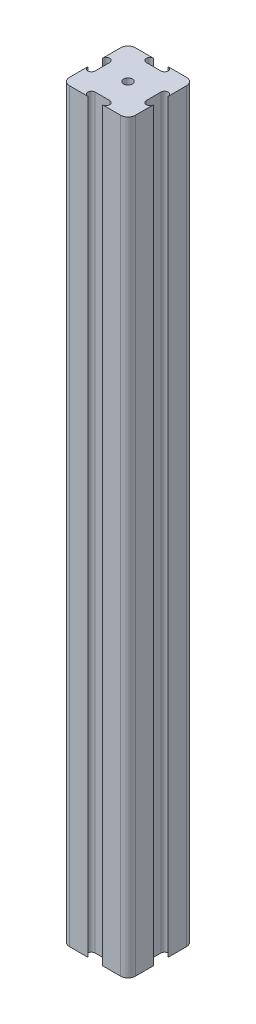
SolidWorks part; units mm, degrees
ref_plane "Front Plane" through (0, 0, 0) normal (0, 0, 1) x (1, 0, 0)
ref_plane "Top Plane" through (0, 0, 0) normal (0, 1, 0) x (1, 0, 0)
ref_plane "Right Plane" through (0, 0, 0) normal (1, 0, 0) x (0, 0, -1)
sketch "Esquisse4" plane through (0, 0, 0) normal (0, 1, 0) x (1, 0, 0)
  line L0 (-17.5, 22.5) -> (-5, 22.5)
  line L1 (22.5, 5) -> (22.5, 17.5)
  line L2 (0, 0) -> (22.5, 0) construction
  line L3 (5, 22.5) -> (17.5, 22.5)
  line L4 (0, 22.5) -> (0, 0) construction
  line L5 (-5, -17.5) -> (5, -17.5)
  line L6 (5, -22.5) -> (17.5, -22.5)
  line L7 (17.5, 5) -> (17.5, -5)
  line L8 (-5, -22.5) -> (-17.5, -22.5)
  line L10 (-5, 20) -> (5, 20) construction
  line L11 (0, 0) -> (0, -28.4326) construction
  line L12 (-5, 17.5) -> (5, 17.5)
  line L13 (17.5, 22.5) -> (17.5, -22.5) construction
  line L14 (-22.5, 17.5) -> (-22.5, 5)
  line L15 (-22.5, -5) -> (-22.5, -17.5)
  line L17 (-17.5, 5) -> (-17.5, -5)
  line L18 (0, 0) -> (-28.2169, 0) construction
  line L19 (22.5, -5) -> (22.5, -17.5)
  arc A0 (17.5, 22.5) -> (22.5, 17.5) centre (17.5, 17.5) cw
  arc A1 (17.5, -22.5) -> (22.5, -17.5) centre (17.5, -17.5) ccw
  arc A2 (-22.5, -17.5) -> (-17.5, -22.5) centre (-17.5, -17.5) ccw
  arc A3 (-17.5, 22.5) -> (-22.5, 17.5) centre (-17.5, 17.5) ccw
  arc A5 (-5, 22.5) -> (-5, 17.5) centre (-5, 20) ccw
  arc A6 (5, 17.5) -> (5, 22.5) centre (5, 20) ccw
  arc A7 (-5, -17.5) -> (-5, -22.5) centre (-5, -20) ccw
  arc A8 (5, -22.5) -> (5, -17.5) centre (5, -20) ccw
  arc A9 (-17.5, -5) -> (-22.5, -5) centre (-20, -5) cw
  arc A10 (22.5, -5) -> (17.5, -5) centre (20, -5) cw
  arc A11 (-17.5, 5) -> (-22.5, 5) centre (-20, 5) ccw
  arc A12 (22.5, 5) -> (17.5, 5) centre (20, 5) ccw
  point P8 (22.5, 22.5)
  point P13 (0, -17.5)
  point P20 (-22.5, 22.5)
  point P23 (0, 20)
  point P44 (0, 0)
  point P45 (0, 0)
  point P46 (0, 0)
  point P47 (28.2853, -8.4459)
  point P51 (0, 0)
  point P52 (0, 0)
  point P53 (-22.5, 5)
  point P54 (-17.5, 5)
  point P55 (-22.5, 5)
  point P56 (17.5, -7.7525)
  point P58 (0, 0)
  point P59 (22.5, -5)
  point P60 (17.5, 5)
  point P61 (22.5, 5)
  point P62 (20, -5)
  point P63 (17.5, -5)
  point P64 (22.5, -5)
  point P65 (17.5, 5)
  point P66 (22.5, 5)
  point P67 (22.5, -5)
  point P68 (17.5, -5)
  point P69 (0, 0)
  dimension "D4" = 5
  dimension "D6" = 5
  dimension "D7" = 5
  dimension "D8" = 5
  dimension "D20" = 10
  dimension "D24" = 12.5
  dimension "D2" = 22.5
  dimension "D3" = 45
  dimension "D5" = 10
  dimension "D10" = 10
  dimension "D11" = 12.5
  dimension "D12" = 22.5
  dimension "D13" = 5
  dimension "D14" = 17.5
  dimension "D15" = 12.5
  dimension "D16" = 45
  dimension "D17" = 2.5
  dimension "D18" = 5
  dimension "D19" = 45
  dimension "D21" = 5
  dimension "D22" = 17.5
  dimension "D23" = 10
  dimension "D25" = 5
extrude "Boss.-Extru.2" add sketch "Esquisse4" along normal blind 510 contours L15 A2 L8 A7 L5 A8 L6 A1 L19 A10 L7 A12 L1 A0 L3 A6 L12 A5 L0 A3 L14 A11 L17 A9
sketch "Esquisse5" plane through (0, 0, 0) normal (0, -1, 0) x (1, 0, 0)
  circle A0 centre (0, 0) radius 3
extrude "Enlèv. mat.-Extru.1" cut sketch "Esquisse5" against normal through all
